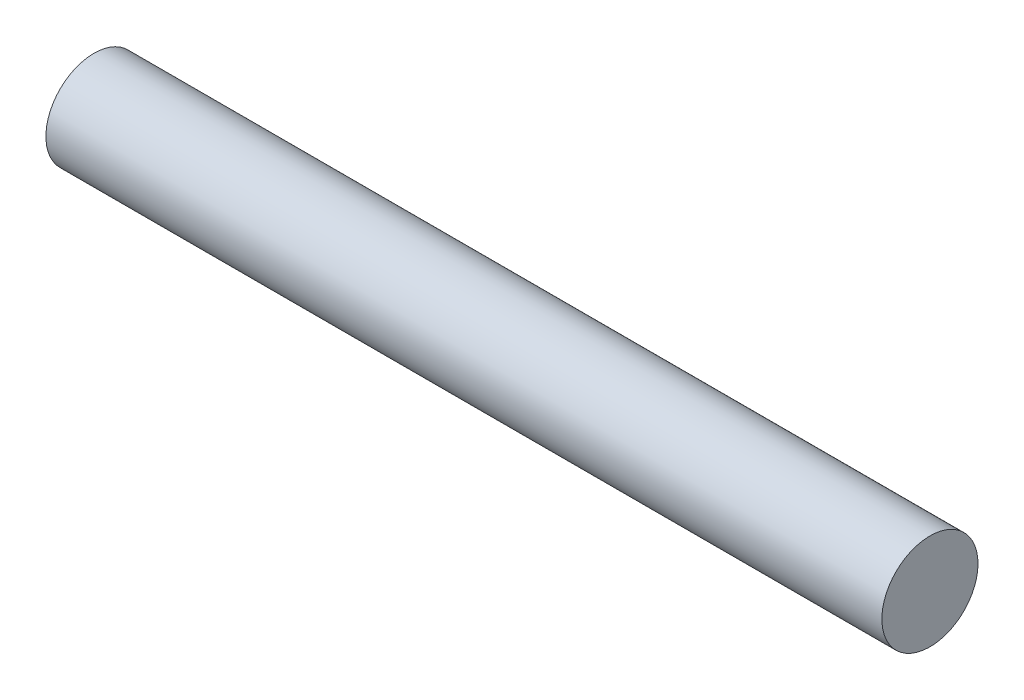
SolidWorks part; units mm, degrees
ref_plane "Front Plane" through (0, 0, 0) normal (0, 0, 1) x (1, 0, 0)
ref_plane "Top Plane" through (0, 0, 0) normal (0, 1, 0) x (1, 0, 0)
ref_plane "Right Plane" through (0, 0, 0) normal (1, 0, 0) x (0, 0, -1)
sketch "Sketch1" plane through (0, 0, 0) normal (1, 0, 0) x (0, 0, -1)
  circle A0 centre (0, 0) radius 1.15
  dimension "D1" = 2.3
extrude "Boss-Extrude1" add sketch "Sketch1" along normal blind 20
